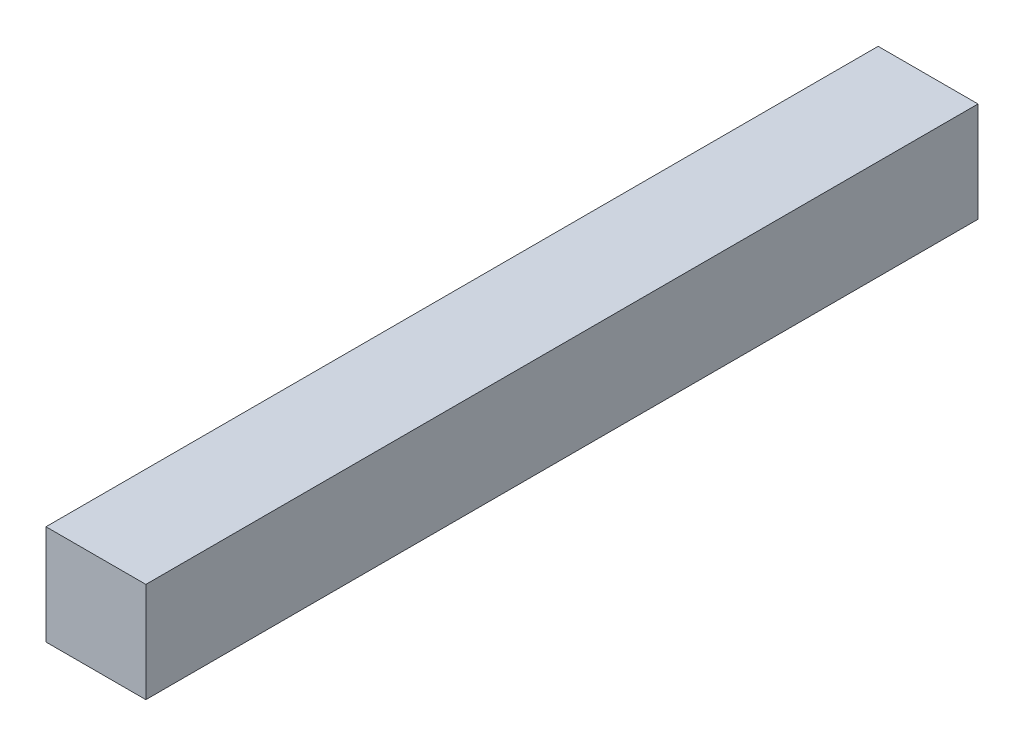
SolidWorks part; units mm, degrees
other "Markup1"
sketch "Sketch2" plane through (15.3981, -15.7652, 240) normal (0.5021, -0.8274, 0.2516) x (0.2779, -0.1212, -0.9529)
ref_plane "Front Plane" through (0, 0, 0) normal (0, 0, 1) x (1, 0, 0)
ref_plane "Top Plane" through (0, 0, 0) normal (0, 1, 0) x (1, 0, 0)
ref_plane "Right Plane" through (0, 0, 0) normal (1, 0, 0) x (0, 0, -1)
sketch "Sketch1" plane through (0, 0, 0) normal (0, 0, 1) x (1, 0, 0)
  line L0 (15, 0) -> (-15, 0) construction
  line L1 (0, -15) -> (0, 15) construction
  line L2 (0, 15) -> (-15, 15)
  line L3 (-15, 15) -> (-15, -15)
  line L4 (-15, -15) -> (15, -15)
  line L5 (15, -15) -> (15, 15)
  line L6 (15, 15) -> (0, 15)
  point P4 (0, 0)
  point P8 (0, 0)
  dimension "D1" = 15
  dimension "D2" = 30
extrude "Boss-Extrude1" add sketch "Sketch1" along normal blind 250
sketch "Sketch3" plane through (0, -15, 0) normal (0, -1, 0) x (-1, 0, 0)
  line L0 (0, -250) -> (0, -245)
  line L1 (15, -250) -> (-15, -250) construction
  line L2 (-10, -245) -> (10, -245)
  line L3 (10, -245) -> (10, -225)
  line L4 (10, -225) -> (-10, -225)
  line L5 (-10, -225) -> (-10, -245)
  line L6 (15, -125) -> (-15, -125) construction
  line L7 (15, -250) -> (15, 0) construction
  line L8 (-15, -250) -> (-15, 0) construction
  line L9 (10, -25) -> (-10, -25)
  line L10 (-10, -25) -> (-10, -5)
  line L11 (-10, -5) -> (10, -5)
  line L12 (10, -5) -> (10, -25)
  point P8 (0, -245)
  dimension "D1" = 5
  dimension "D2" = 20
  dimension "D3" = 20
extrude "Cut-Extrude1" cut sketch "Sketch3" against normal blind 20 contours L4 L5 L2 L3 | L12 L11 L10 L9
